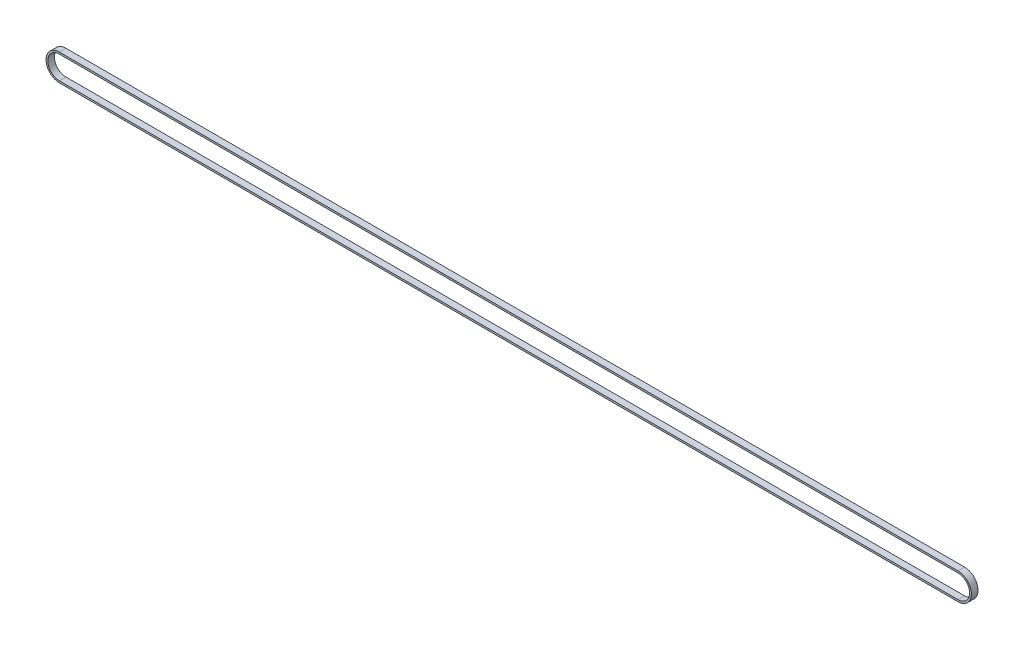
SolidWorks part; units mm, degrees
material "Rubber"
ref_plane "Front Plane" through (0, 0, 0) normal (0, 0, 1) x (1, 0, 0)
ref_plane "Top Plane" through (0, 0, 0) normal (0, 1, 0) x (1, 0, 0)
ref_plane "Right Plane" through (0, 0, 0) normal (1, 0, 0) x (0, 0, -1)
sketch "Sketch1" plane through (0, 0, 0) normal (0, 0, 1) x (1, 0, 0)
  line L0 (0, 0) -> (682, 0) construction
  line L1 (0, 8.75) -> (682, 8.75)
  line L2 (682, -8.75) -> (0, -8.75)
  arc A0 (0, 8.75) -> (0, -8.75) centre (0, 0) ccw
  arc A1 (682, -8.75) -> (682, 8.75) centre (682, 0) ccw
  dimension "D1" = 17.5
  dimension "D2" = 682
extrude "Extrude-Thin1" add sketch "Sketch1" along normal mid plane 5 thin thin type one direction wall 1.38
